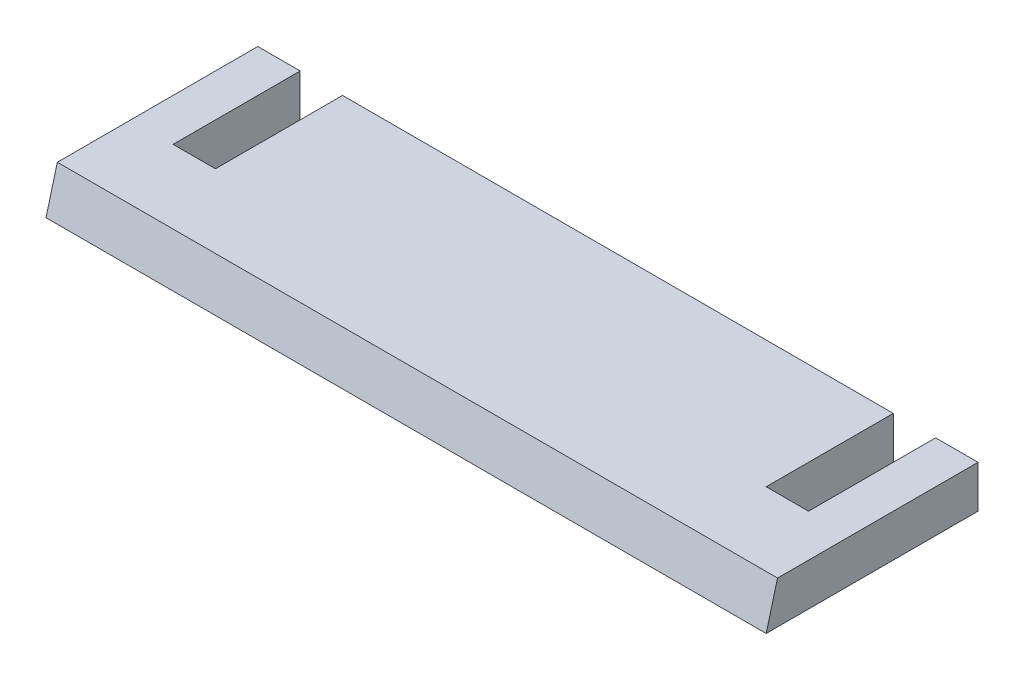
SolidWorks part; units mm, degrees
ref_plane "Front Plane" through (0, 0, 0) normal (0, 0, 1) x (1, 0, 0)
ref_plane "Top Plane" through (0, 0, 0) normal (0, 1, 0) x (1, 0, 0)
ref_plane "Right Plane" through (0, 0, 0) normal (1, 0, 0) x (0, 0, -1)
sketch "Sketch1" plane through (0, 0, 0) normal (0, 1, 0) x (1, 0, 0)
  line L0 (0, 0) -> (0, 25) construction
  line L1 (85, -25) -> (-85, -25)
  line L2 (85, -25) -> (85, 25)
  line L3 (85, 25) -> (75, 25)
  line L4 (-85, -25) -> (-85, 25)
  line L5 (85, -25) -> (-85, 25) construction
  line L6 (85, 25) -> (-85, -25) construction
  line L7 (75, -5) -> (65, -5)
  line L9 (-75, 25) -> (-75, -5)
  line L10 (-75, -5) -> (-65, -5)
  line L11 (-65, 25) -> (-65, -5)
  line L12 (65, 25) -> (65, -5)
  line L13 (75, 25) -> (75, -5)
  line L14 (-75, 25) -> (-85, 25)
  line L15 (65, 25) -> (-65, 25)
  point P0 (0, 0)
  dimension "D1" = 170
  dimension "D2" = 50
  dimension "D3" = 10
  dimension "D4" = 30
  dimension "D5" = 10
extrude "Boss-Extrude1" add sketch "Sketch1" along normal blind 10
draft "Draft1" type of draft neutral plane draft angle 15 faces to draft 1 face at (0, 5, 25) neutral plane through (0, 0, 0) neutral plane normal (0, -1, 0) reverse direction yes parameters "D1"=15
